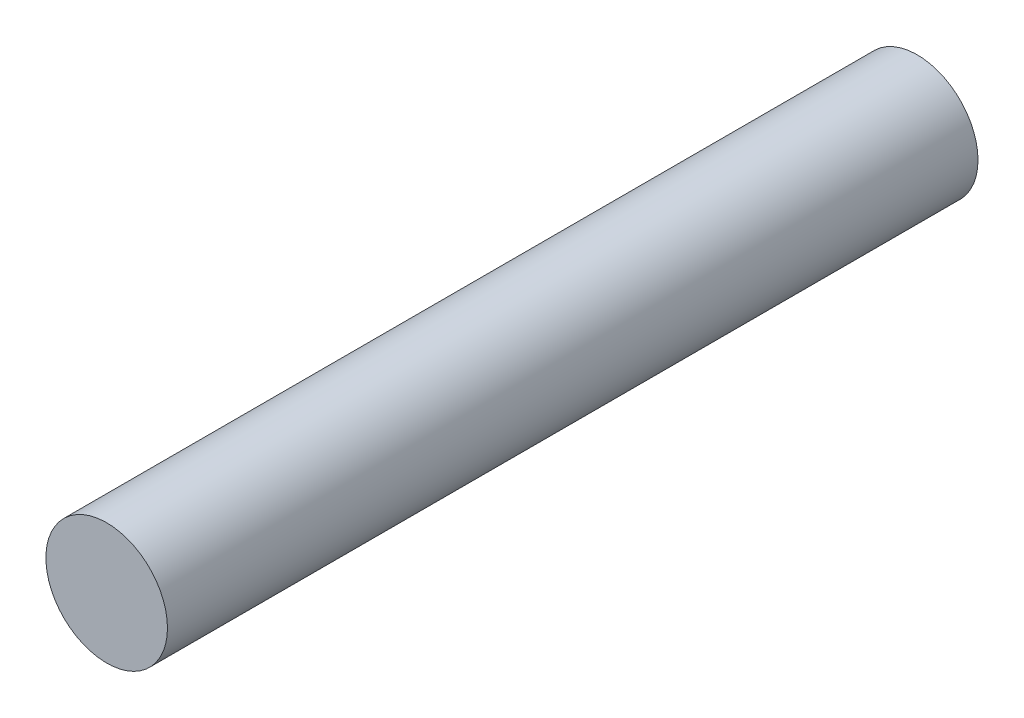
SolidWorks part; units mm, degrees
material "Aleación 1060"
ref_plane "Alzado" through (0, 0, 0) normal (0, 0, 1) x (1, 0, 0)
ref_plane "Planta" through (0, 0, 0) normal (0, 1, 0) x (1, 0, 0)
ref_plane "Vista lateral" through (0, 0, 0) normal (1, 0, 0) x (0, 0, -1)
sketch "Croquis1" plane through (0, 0, 0) normal (0, 0, 1) x (1, 0, 0)
  circle A0 centre (0, 0) radius 9.525
  dimension "D1" = 19.05
extrude "Saliente-Extruir1" add sketch "Croquis1" along normal blind 127
sketch "Croquis3" plane through (0, 0, 0) normal (0, 0, -1) x (-1, 0, 0)
  line L0 (0, 0) -> (0, 9.525)
  circle A0 centre (0, 0) radius 9.525 construction
ref_point "Punto1"
